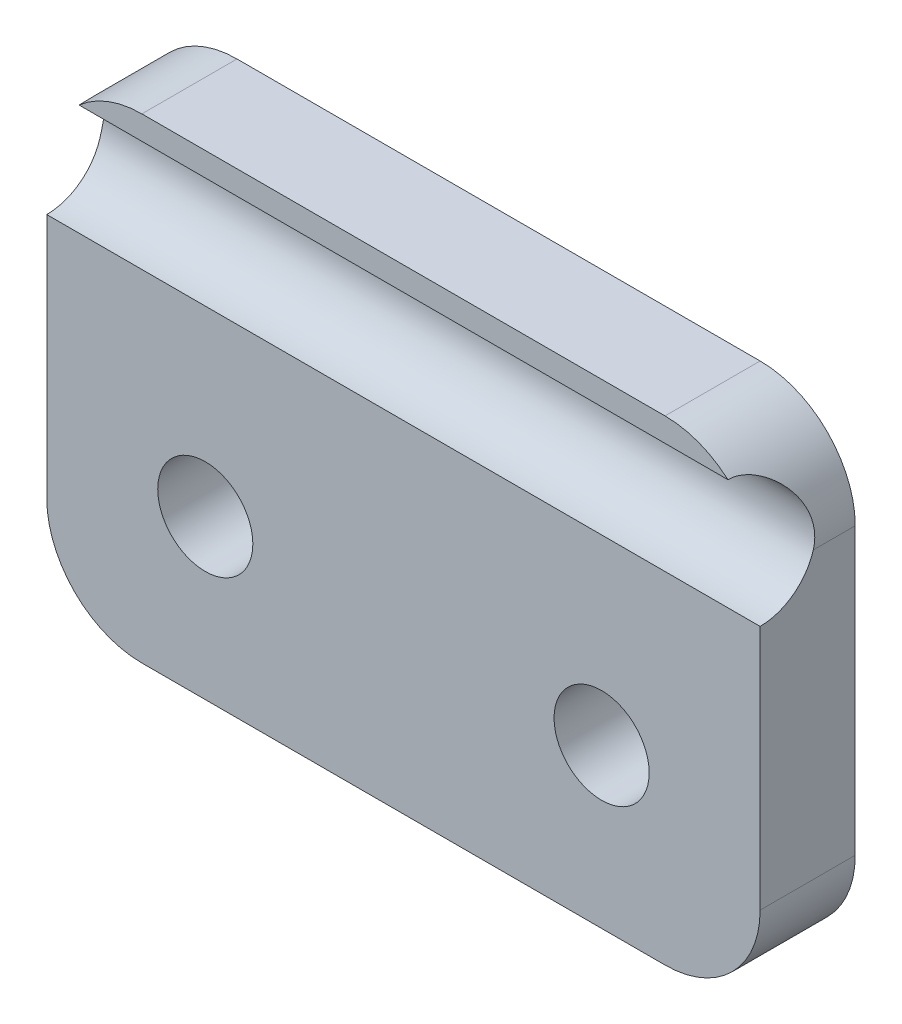
SolidWorks part; units mm, degrees
ref_plane "Ön Düzlem" through (0, 0, 0) normal (0, 0, 1) x (1, 0, 0)
ref_plane "Üst Düzlem" through (0, 0, 0) normal (0, 1, 0) x (1, 0, 0)
ref_plane "Sağ Düzlem" through (0, 0, 0) normal (1, 0, 0) x (0, 0, -1)
sketch "Çizim1" plane through (0, 0, 0) normal (0, 0, 1) x (1, 0, 0)
  line L1 (-16.5, -15) -> (16.5, -15)
  line L2 (-22.5, -9) -> (-22.5, 9)
  line L3 (-16.5, 15) -> (16.5, 15)
  line L4 (22.5, -9) -> (22.5, 9)
  line L5 (-22.5, -15) -> (22.5, 15) construction
  line L6 (-22.5, 15) -> (22.5, -15) construction
  arc A0 (22.5, 9) -> (16.5, 15) centre (16.5, 9) ccw
  arc A1 (-22.5, 9) -> (-16.5, 15) centre (-16.5, 9) cw
  arc A2 (-22.5, -9) -> (-16.5, -15) centre (-16.5, -9) ccw
  arc A3 (16.5, -15) -> (22.5, -9) centre (16.5, -9) ccw
  point P0 (0, 0)
  dimension "D3" = 6
  dimension "D4" = 6
  dimension "D1" = 30
  dimension "D2" = 45
extrude "Yükseklik-Ekstrüzyon1" add sketch "Çizim1" along normal blind 6
sketch "Çizim2" plane through (0, 0, 0) normal (1, 0, 0) x (0, 0, -1)
  line L0 (-6, -9) -> (-6, 9) construction
  line L1 (-6, 15) -> (0, 15) construction
  circle A0 centre (-6, 10) radius 3.5
  dimension "D2" = 7
  dimension "D1" = 5
extrude "Kes-Ekstrüzyon1" cut sketch "Çizim2" against normal through all and the other way through all
sketch "Çizim3" plane through (0, 0, 0) normal (0, 0, -1) x (-1, 0, 0)
  line L0 (22.5, 6.5) -> (22.5, -9) construction
  line L1 (-22.5, -9) -> (-22.5, 6.5) construction
  line L2 (16.5, -15) -> (-16.5, -15) construction
  circle A0 centre (12.5, -5) radius 3
  circle A1 centre (-12.5, -5) radius 3
  dimension "D4" = 6
  dimension "D1" = 10
  dimension "D2" = 10
  dimension "D3" = 10
extrude "Kes-Ekstrüzyon2" cut sketch "Çizim3" against normal blind 44
